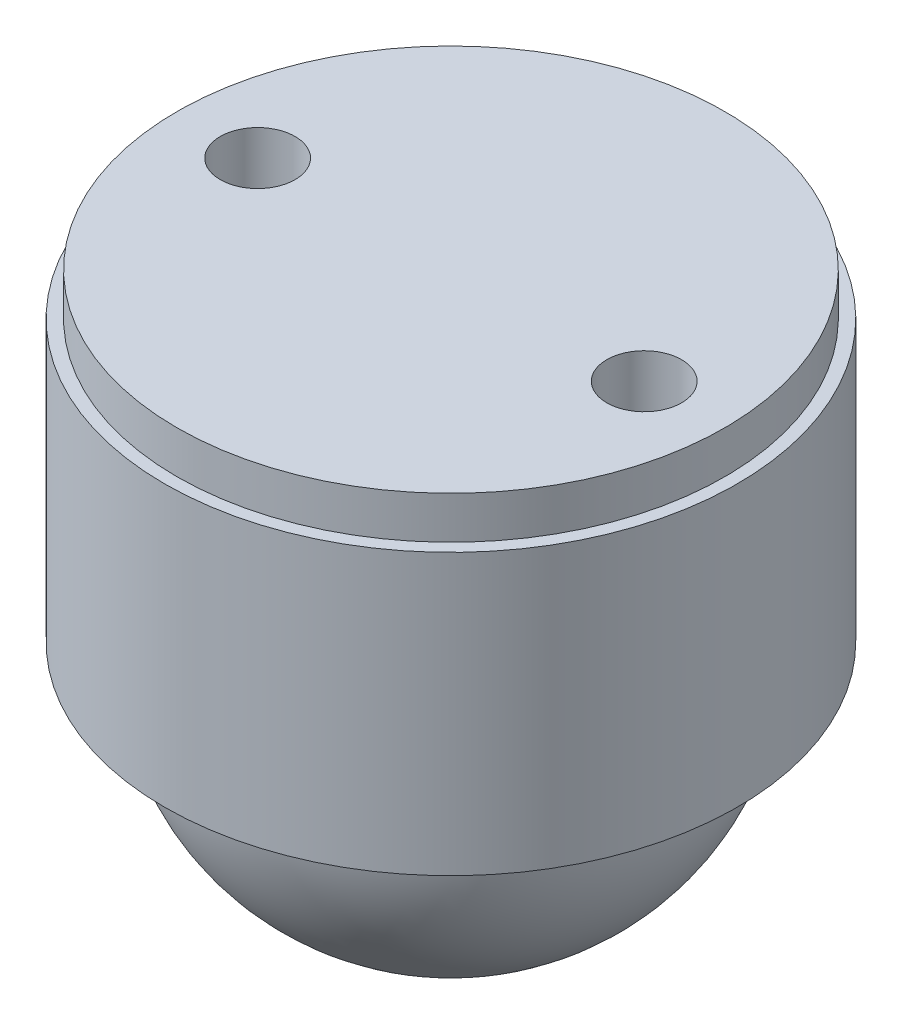
SolidWorks part; units mm, degrees
ref_plane "Front Plane" through (0, 0, 0) normal (0, 0, 1) x (1, 0, 0)
ref_plane "Top Plane" through (0, 0, 0) normal (0, 1, 0) x (1, 0, 0)
ref_plane "Right Plane" through (0, 0, 0) normal (1, 0, 0) x (0, 0, -1)
sketch "Sketch1" plane through (0, 0, 0) normal (0, 1, 0) x (1, 0, 0)
  line L0 (0, 9.525) -> (0, -9.525)
  arc A0 (0, -9.525) -> (0, 9.525) centre (0, 0) ccw
  dimension "D1" = 9.525
  dimension "D2" = 19.05
revolve "Revolve1" add sketch "Sketch1" angle 360 about L0
sketch "Sketch2" plane through (0, 0, 0) normal (0, 1, 0) x (1, 0, 0)
  circle A0 centre (0, 0) radius 11.475
  dimension "D1" = 22.95
extrude "Boss-Extrude1" add sketch "Sketch2" along normal blind 11.225
sketch "Sketch5" plane through (0, 11.225, 0) normal (0, 1, 0) x (1, 0, 0)
  circle A0 centre (0, 0) radius 10.98
  dimension "D1" = 21.96
extrude "Boss-Extrude3" add sketch "Sketch5" along normal blind 1.7
sketch "Sketch6" plane through (0, 12.925, 0) normal (0, 1, 0) x (1, 0, 0)
  circle A0 centre (7.747, 0) radius 1.5
  circle A1 centre (-7.747, 0) radius 1.5
  circle A2 centre (0, 0) radius 10.98 construction
  dimension "D3" = 3
  dimension "D4" = 3
  dimension "D1" = 15.494
  dimension "D2" = 7.747
  dimension "D5" = 7.747
  dimension "D6" = 7.747
extrude "Cut-Extrude4" cut sketch "Sketch6" against normal blind 5
